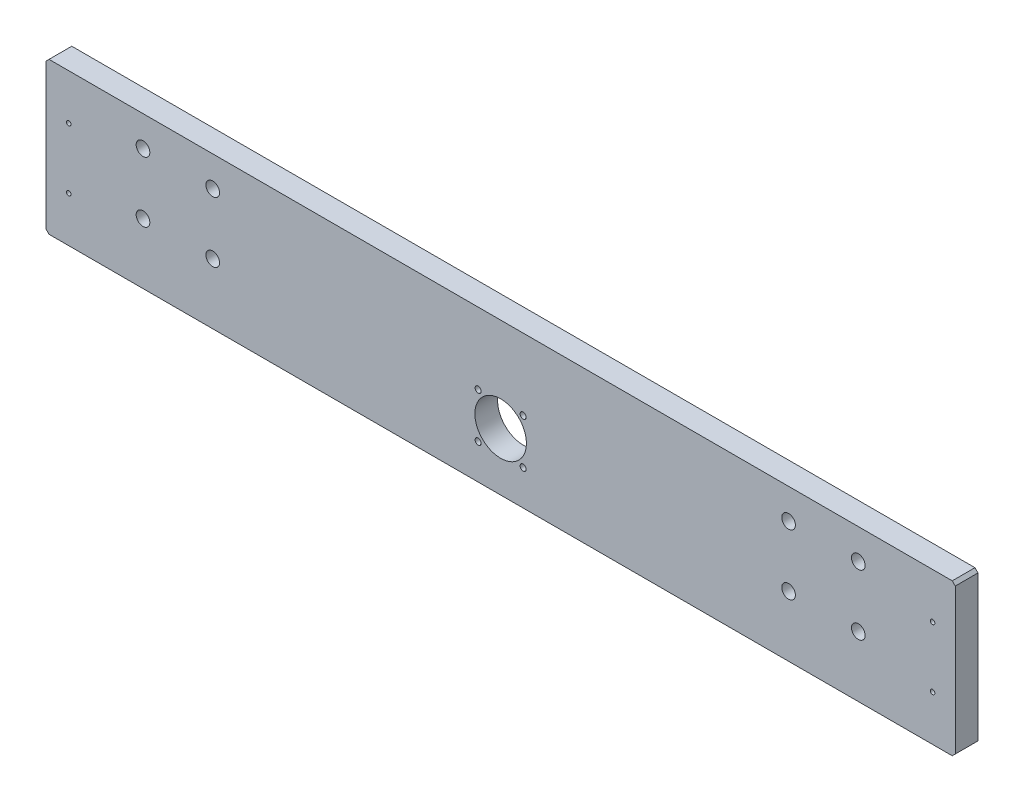
SolidWorks part; units mm, degrees
ref_plane "Piano frontale" through (0, 0, 0) normal (0, 0, 1) x (1, 0, 0)
ref_plane "Piano superiore" through (0, 0, 0) normal (0, 1, 0) x (1, 0, 0)
ref_plane "Piano destro" through (0, 0, 0) normal (1, 0, 0) x (0, 0, -1)
sketch "Schizzo1" plane through (0, 0, 0) normal (0, 0, 1) x (1, 0, 0)
  line L0 (300, 100) -> (300, 0) construction
  line L1 (2, 0) -> (598, 0)
  line L2 (0, 2) -> (0, 98)
  line L3 (2, 100) -> (598, 100)
  line L4 (600, 2) -> (600, 98)
  line L5 (300, 38) -> (270.4474, 67.5526) construction
  line L6 (64, 80) -> (536, 80) construction
  line L7 (300, 38) -> (318.5099, 38) construction
  line L8 (87, 80) -> (87, 40) construction
  line L9 (211.2881, 38) -> (400.934, 38) construction
  line L21 (0, 98) -> (2, 100)
  line L22 (2, 0) -> (0, 2)
  line L23 (598, 0) -> (600, 2)
  line L24 (598, 100) -> (600, 98)
  circle A0 centre (300, 38) radius 17
  circle A1 centre (300, 38) radius 21 construction
  circle A2 centre (314.8492, 52.8492) radius 2
  circle A3 centre (110, 40) radius 4.5
  circle A4 centre (314.8492, 23.1508) radius 2
  circle A5 centre (285.1508, 23.1508) radius 2
  circle A6 centre (110, 80) radius 4.5
  circle A7 centre (536, 40) radius 4.5
  circle A8 centre (64, 40) radius 4.5
  circle A9 centre (64, 80) radius 4.5
  circle A10 centre (490, 40) radius 4.5
  circle A11 centre (15, 30) radius 1.5
  circle A12 centre (585, 30) radius 1.5
  circle A13 centre (285.1508, 52.8492) radius 2
  circle A14 centre (490, 80) radius 4.5
  circle A15 centre (536, 80) radius 4.5
  circle A17 centre (585, 70) radius 1.5
  circle A18 centre (15, 70) radius 1.5
  point P0 (0, 0)
  point P1 (600, 100)
  point P2 (0, 100)
  point P3 (600, 0)
  point P13 (285.1508, 52.8492)
  point P14 (314.8492, 52.8492)
  point P15 (285.1508, 23.1508)
  point P17 (314.8492, 23.1508)
  dimension "D4" = 34
  dimension "D10" = 64
  dimension "D15" = 3
  dimension "D17" = 4
  dimension "D8" = 42
  dimension "D1" = 100
  dimension "D2" = 600
  dimension "D3" = 38
  dimension "D5" = 45
  dimension "D6" = 20
  dimension "D7" = 40
  dimension "D9" = 23
  dimension "D14" = 30
  dimension "D16" = 15
extrude "Estrusione-Estrusione1" add sketch "Schizzo1" against normal blind 15
sketch "Sketch1" plane through (0, 0, 0) normal (0, -1, 0) x (1, 0, 0)
  line L0 (2, -7.5) -> (598, -7.5) construction
  line L1 (2, -15) -> (2, 0) construction
  line L2 (598, -15) -> (598, 0) construction
  line L3 (300, 0) -> (300, -15) construction
  line L4 (2, 0) -> (598, 0) construction
  line L5 (2, -15) -> (598, -15) construction
  line L6 (0, -15) -> (0, 0) construction
  point P12 (30, -7.5)
  point P15 (570, -7.5)
  dimension "D1" = 30
hole_wizard "M8 Tapped Hole1" positions "3DSketch2" profile "Sketch2" tap size "M8" standard "ISO"
sketch3d "3DSketch2"
  point P0 (30, 0, -7.5)
  point P3 (570, 0, -7.5)
sketch "Sketch2" plane through (30, 0, -7.5) normal (1, 0, 0) x (0, 0, -1)
  line L0 (0, 0) -> (0, 25.7929)
  line L1 (0, 25.7929) -> (3.4, 23.75)
  line L2 (3.4, 23.75) -> (3.4, 0)
  line L5 (3.4, 0) -> (0, 0)
  line L10 (0, 25.7929) -> (-3.4, 23.75) construction
  line L11 (0, -6.35) -> (0, 107.95) construction
  dimension "Tap Drill Dia." = 6.8
  dimension "Tap Drill Depth" = 23.75
  dimension "Drill Angle" = 118
